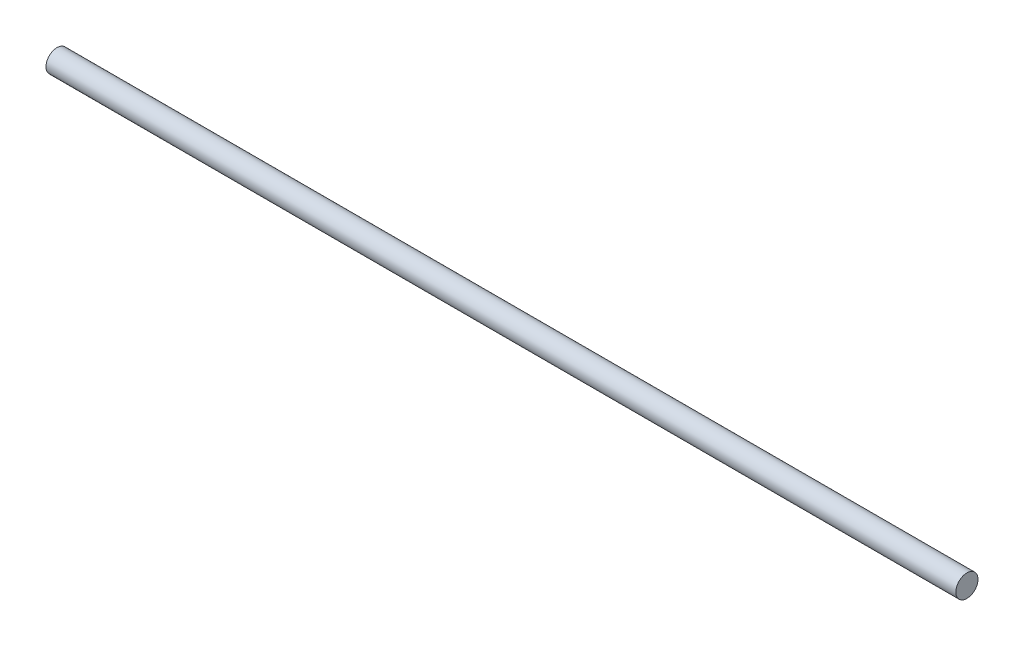
SolidWorks part; units mm, degrees
ref_plane "Front Plane" through (0, 0, 0) normal (0, 0, 1) x (1, 0, 0)
ref_plane "Top Plane" through (0, 0, 0) normal (0, 1, 0) x (1, 0, 0)
ref_plane "Right Plane" through (0, 0, 0) normal (1, 0, 0) x (0, 0, -1)
sketch "Sketch2" plane through (0, 0, 0) normal (1, 0, 0) x (0, 0, -1)
  circle A0 centre (0, 0) radius 0.975
  dimension "D1" = 1.95
extrude "Boss-Extrude1" add sketch "Sketch2" along normal blind 80
